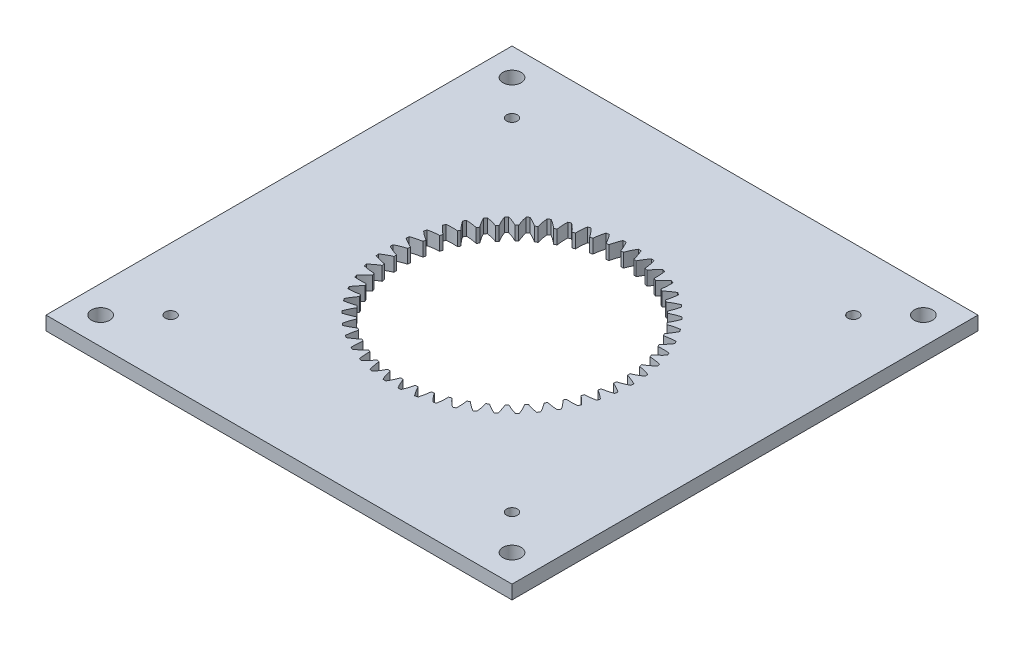
SolidWorks part; units mm, degrees
material "Acrylic (Medium-high impact)"
ref_plane "Front Plane" through (0, 0, 0) normal (0, 0, 1) x (1, 0, 0)
ref_plane "Top Plane" through (0, 0, 0) normal (0, 1, 0) x (1, 0, 0)
ref_plane "Right Plane" through (0, 0, 0) normal (1, 0, 0) x (0, 0, -1)
sketch "Sketch1" plane through (0, 0, 0) normal (0, 1, 0) x (1, 0, 0)
  line L1 (-50.8, 50.8) -> (50.8, 50.8)
  line L2 (-50.8, 50.8) -> (-50.8, -50.8)
  line L3 (-50.8, -50.8) -> (50.8, -50.8)
  line L4 (50.8, 50.8) -> (50.8, -50.8)
  line L5 (-50.8, 50.8) -> (50.8, -50.8) construction
  line L6 (-50.8, -50.8) -> (50.8, 50.8) construction
  point P0 (0, 0)
  dimension "D1" = 101.6
  dimension "D2" = 101.6
extrude "Boss-Extrude1" add sketch "Sketch1" along normal blind 3
extrude "Cut-Extrude2" cut sketch "Sketch3" against normal through all
sketch "Sketch3" plane through (-45.1098, 10, -77.0657) normal (0, 1, 0) x (1, 0, 0)
  arc A17 (36.701, -52.1979) -> (36.5419, -54.6472) centre (49.0349, -54.2291) ccw
  arc A18 (36.009, -54.8582) -> (34.2163, -53.1817) centre (26.6157, -63.1054) ccw
  arc A19 (36.5419, -54.6472) -> (36.009, -54.8582) centre (45.1098, -77.0657) ccw
  arc A20 (34.2163, -53.1817) -> (33.6506, -53.4479) centre (45.1098, -77.0657) ccw
  arc A25 (31.3088, -54.7353) -> (30.7808, -55.0704) centre (45.1098, -77.0657) ccw
  arc A26 (33.6506, -53.4479) -> (33.7997, -55.8978) centre (46.1418, -53.9172) ccw
  arc A27 (33.7997, -55.8978) -> (33.2974, -56.1739) centre (45.1098, -77.0657) ccw
  arc A28 (33.2974, -56.1739) -> (31.3088, -54.7353) centre (25.0119, -65.5334) ccw
  arc A29 (39.8841, -51.3401) -> (39.4193, -53.7501) centre (51.8662, -54.9011) ccw
  arc A30 (38.8641, -53.8927) -> (37.2957, -52.0047) centre (28.5113, -60.8976) ccw
  arc A31 (39.4193, -53.7501) -> (38.8641, -53.8927) centre (45.1098, -77.0657) ccw
  arc A32 (37.2957, -52.0047) -> (36.701, -52.1979) centre (45.1098, -77.0657) ccw
  arc A33 (43.1496, -50.888) -> (42.3864, -53.2208) centre (54.5909, -55.9227) ccw
  arc A34 (41.8177, -53.2926) -> (40.4983, -51.223) centre (30.6685, -58.9447) ccw
  arc A35 (42.3864, -53.2208) -> (41.8177, -53.2926) centre (45.1098, -77.0657) ccw
  arc A36 (40.4983, -51.223) -> (39.8841, -51.3401) centre (45.1098, -77.0657) ccw
  arc A37 (46.446, -50.8488) -> (45.3964, -53.0675) centre (57.166, -57.2777) ccw
  arc A38 (44.8232, -53.0675) -> (43.7736, -50.8488) centre (33.0536, -57.2777) ccw
  arc A39 (45.3964, -53.0675) -> (44.8232, -53.0675) centre (45.1098, -77.0657) ccw
  arc A40 (43.7736, -50.8488) -> (43.1496, -50.888) centre (45.1098, -77.0657) ccw
  arc A41 (49.7213, -51.223) -> (48.4019, -53.2926) centre (59.5511, -58.9447) ccw
  arc A42 (47.8333, -53.2208) -> (47.07, -50.888) centre (35.6288, -55.9227) ccw
  arc A43 (48.4019, -53.2926) -> (47.8333, -53.2208) centre (45.1098, -77.0657) ccw
  arc A44 (47.07, -50.888) -> (46.446, -50.8488) centre (45.1098, -77.0657) ccw
  arc A45 (52.9239, -52.0047) -> (51.3555, -53.8927) centre (61.7083, -60.8976) ccw
  arc A46 (50.8003, -53.7501) -> (50.3355, -51.3401) centre (38.3534, -54.9011) ccw
  arc A47 (51.3555, -53.8927) -> (50.8003, -53.7501) centre (45.1098, -77.0657) ccw
  arc A48 (50.3355, -51.3401) -> (49.7213, -51.223) centre (45.1098, -77.0657) ccw
  arc A49 (56.0033, -53.1817) -> (54.2106, -54.8582) centre (63.6039, -63.1054) ccw
  arc A50 (53.6777, -54.6472) -> (53.5186, -52.1979) centre (41.1847, -54.2291) ccw
  arc A51 (54.2106, -54.8582) -> (53.6777, -54.6472) centre (45.1098, -77.0657) ccw
  arc A52 (53.5186, -52.1979) -> (52.9239, -52.0047) centre (45.1098, -77.0657) ccw
  arc A53 (58.9108, -54.7353) -> (56.9222, -56.1739) centre (65.2077, -65.5334) ccw
  arc A54 (56.4199, -55.8978) -> (56.569, -53.4479) centre (44.0778, -53.9172) ccw
  arc A55 (56.9222, -56.1739) -> (56.4199, -55.8978) centre (45.1098, -77.0657) ccw
  arc A56 (56.569, -53.4479) -> (56.0033, -53.1817) centre (45.1098, -77.0657) ccw
  arc A57 (61.6007, -56.6411) -> (59.4475, -57.8192) centre (66.4946, -68.1433) ccw
  arc A58 (58.9838, -57.4823) -> (59.4388, -55.0704) centre (46.9873, -53.9704) ccw
  arc A59 (59.4475, -57.8192) -> (58.9838, -57.4823) centre (45.1098, -77.0657) ccw
  arc A60 (59.4388, -55.0704) -> (58.9108, -54.7353) centre (45.1098, -77.0657) ccw
  arc A61 (64.0306, -58.8691) -> (61.7467, -59.7679) centre (67.4443, -70.8939) ccw
  arc A62 (61.3288, -59.3756) -> (62.0825, -57.0397) centre (49.8671, -54.3878) ccw
  arc A63 (61.7467, -59.7679) -> (61.3288, -59.3756) centre (45.1098, -77.0657) ccw
  arc A64 (62.0825, -57.0397) -> (61.6007, -56.6411) centre (45.1098, -77.0657) ccw
  arc A65 (66.162, -61.384) -> (63.7835, -61.9895) centre (68.0417, -73.7418) ccw
  arc A66 (63.4181, -61.5478) -> (64.4586, -59.3249) centre (52.6719, -55.1629) ccw
  arc A67 (63.7835, -61.9895) -> (63.4181, -61.5478) centre (45.1098, -77.0657) ccw
  arc A68 (64.4586, -59.3249) -> (64.0306, -58.8691) centre (45.1098, -77.0657) ccw
  arc A69 (67.9615, -64.1462) -> (65.5258, -64.4488) centre (68.2775, -76.6422) ccw
  arc A70 (65.2187, -63.9648) -> (66.5296, -61.8898) centre (55.3574, -56.2834) ccw
  arc A71 (65.5258, -64.4488) -> (65.2187, -63.9648) centre (45.1098, -77.0657) ccw
  arc A72 (66.5296, -61.8898) -> (66.162, -61.384) centre (45.1098, -77.0657) ccw
  arc A73 (69.4005, -67.1121) -> (66.9461, -67.1071) centre (68.1479, -79.5492) ccw
  arc A74 (66.7021, -66.5884) -> (68.2627, -64.6941) centre (57.8813, -57.7316) ccw
  arc A75 (66.9461, -67.1071) -> (66.7021, -66.5884) centre (45.1098, -77.0657) ccw
  arc A76 (68.2627, -64.6941) -> (67.9615, -64.1462) centre (45.1098, -77.0657) ccw
  arc A77 (70.4565, -70.235) -> (68.0221, -69.9224) centre (67.655, -82.417) ccw
  arc A78 (67.845, -69.3773) -> (69.6307, -67.6935) centre (60.2038, -59.4847) ccw
  arc A79 (68.0221, -69.9224) -> (67.845, -69.3773) centre (45.1098, -77.0657) ccw
  arc A80 (69.6307, -67.6935) -> (69.4005, -67.1121) centre (45.1098, -77.0657) ccw
  arc A81 (71.1128, -73.4657) -> (68.7367, -72.8504) centre (66.8065, -85.2005) ccw
  arc A82 (68.6293, -72.2874) -> (70.612, -70.8407) centre (62.2883, -61.5152) ccw
  arc A83 (68.7367, -72.8504) -> (68.6293, -72.2874) centre (45.1098, -77.0657) ccw
  arc A84 (70.612, -70.8407) -> (70.4565, -70.235) centre (45.1098, -77.0657) ccw
  arc A85 (71.3589, -76.7531) -> (69.0787, -75.8449) centre (65.6158, -87.8557) ccw
  arc A86 (69.0427, -75.2728) -> (71.1911, -74.086) centre (64.1018, -63.7908) ccw
  arc A87 (69.0787, -75.8449) -> (69.0427, -75.2728) centre (45.1098, -77.0657) ccw
  arc A88 (71.1911, -74.086) -> (71.1128, -73.4657) centre (45.1098, -77.0657) ccw
  arc A89 (71.1911, -80.0455) -> (69.0427, -78.8586) centre (64.1018, -90.3407) ccw
  arc A90 (69.0787, -78.2866) -> (71.3589, -77.3784) centre (65.6158, -66.2758) ccw
  arc A91 (69.0427, -78.8586) -> (69.0787, -78.2866) centre (45.1098, -77.0657) ccw
  arc A92 (71.3589, -77.3784) -> (71.3589, -76.7531) centre (45.1098, -77.0657) ccw
  arc A93 (70.612, -83.2908) -> (68.6293, -81.8441) centre (62.2883, -92.6163) ccw
  arc A94 (68.7367, -81.2811) -> (71.1128, -80.6658) centre (66.8065, -68.931) ccw
  arc A95 (68.6293, -81.8441) -> (68.7367, -81.2811) centre (45.1098, -77.0657) ccw
  arc A96 (71.1128, -80.6658) -> (71.1911, -80.0455) centre (45.1098, -77.0657) ccw
  arc A97 (69.6307, -86.438) -> (67.845, -84.7542) centre (60.2038, -94.6467) ccw
  arc A98 (68.0221, -84.2091) -> (70.4565, -83.8964) centre (67.655, -71.7144) ccw
  arc A99 (67.845, -84.7542) -> (68.0221, -84.2091) centre (45.1098, -77.0657) ccw
  arc A100 (70.4565, -83.8964) -> (70.612, -83.2908) centre (45.1098, -77.0657) ccw
  arc A101 (68.2627, -89.4374) -> (66.7021, -87.543) centre (57.8813, -96.3999) ccw
  arc A102 (66.9461, -87.0244) -> (69.4005, -87.0194) centre (68.1479, -74.5823) ccw
  arc A103 (66.7021, -87.543) -> (66.9461, -87.0244) centre (45.1098, -77.0657) ccw
  arc A104 (69.4005, -87.0194) -> (69.6307, -86.438) centre (45.1098, -77.0657) ccw
  arc A105 (66.5296, -92.2417) -> (65.2187, -90.1666) centre (55.3574, -97.8481) ccw
  arc A106 (65.5258, -89.6827) -> (67.9615, -89.9853) centre (68.2775, -77.4893) ccw
  arc A107 (65.2187, -90.1666) -> (65.5258, -89.6827) centre (45.1098, -77.0657) ccw
  arc A108 (67.9615, -89.9853) -> (68.2627, -89.4374) centre (45.1098, -77.0657) ccw
  arc A109 (64.4586, -94.8066) -> (63.4181, -92.5836) centre (52.6719, -98.9686) ccw
  arc A110 (63.7835, -92.142) -> (66.162, -92.7475) centre (68.0417, -80.3897) ccw
  arc A111 (63.4181, -92.5836) -> (63.7835, -92.142) centre (45.1098, -77.0657) ccw
  arc A112 (66.162, -92.7475) -> (66.5296, -92.2417) centre (45.1098, -77.0657) ccw
  arc A113 (62.0825, -97.0918) -> (61.3288, -94.7559) centre (49.8671, -99.7437) ccw
  arc A114 (61.7467, -94.3636) -> (64.0306, -95.2624) centre (67.4443, -83.2376) ccw
  arc A115 (61.3288, -94.7559) -> (61.7467, -94.3636) centre (45.1098, -77.0657) ccw
  arc A116 (64.0306, -95.2624) -> (64.4586, -94.8066) centre (45.1098, -77.0657) ccw
  arc A117 (59.4388, -99.0611) -> (58.9838, -96.6492) centre (46.9873, -100.1611) ccw
  arc A118 (59.4475, -96.3123) -> (61.6007, -97.4903) centre (66.4946, -85.9882) ccw
  arc A119 (58.9838, -96.6492) -> (59.4475, -96.3123) centre (45.1098, -77.0657) ccw
  arc A120 (61.6007, -97.4903) -> (62.0825, -97.0918) centre (45.1098, -77.0657) ccw
  arc A121 (56.569, -100.6836) -> (56.4199, -98.2337) centre (44.0778, -100.2143) ccw
  arc A122 (56.9222, -97.9575) -> (58.9108, -99.3961) centre (65.2077, -88.598) ccw
  arc A123 (56.4199, -98.2337) -> (56.9222, -97.9575) centre (45.1098, -77.0657) ccw
  arc A124 (58.9108, -99.3961) -> (59.4388, -99.0611) centre (45.1098, -77.0657) ccw
  arc A125 (53.5186, -101.9335) -> (53.6777, -99.4843) centre (41.1847, -99.9024) ccw
  arc A126 (54.2106, -99.2733) -> (56.0033, -100.9498) centre (63.6039, -91.026) ccw
  arc A127 (53.6777, -99.4843) -> (54.2106, -99.2733) centre (45.1098, -77.0657) ccw
  arc A128 (56.0033, -100.9498) -> (56.569, -100.6836) centre (45.1098, -77.0657) ccw
  arc A129 (50.3355, -102.7914) -> (50.8003, -100.3814) centre (38.3534, -99.2304) ccw
  arc A130 (51.3555, -100.2388) -> (52.9239, -102.1268) centre (61.7083, -93.2339) ccw
  arc A131 (50.8003, -100.3814) -> (51.3555, -100.2388) centre (45.1098, -77.0657) ccw
  arc A132 (52.9239, -102.1268) -> (53.5186, -101.9335) centre (45.1098, -77.0657) ccw
  arc A133 (47.07, -103.2434) -> (47.8333, -100.9107) centre (35.6288, -98.2088) ccw
  arc A134 (48.4019, -100.8389) -> (49.7213, -102.9085) centre (59.5511, -95.1867) ccw
  arc A135 (47.8333, -100.9107) -> (48.4019, -100.8389) centre (45.1098, -77.0657) ccw
  arc A136 (49.7213, -102.9085) -> (50.3355, -102.7914) centre (45.1098, -77.0657) ccw
  arc A137 (43.7736, -103.2827) -> (44.8232, -101.064) centre (33.0536, -96.8538) ccw
  arc A138 (45.3964, -101.064) -> (46.446, -103.2827) centre (57.166, -96.8538) ccw
  arc A139 (44.8232, -101.064) -> (45.3964, -101.064) centre (45.1098, -77.0657) ccw
  arc A140 (46.446, -103.2827) -> (47.07, -103.2434) centre (45.1098, -77.0657) ccw
  arc A141 (40.4983, -102.9085) -> (41.8177, -100.8389) centre (30.6685, -95.1867) ccw
  arc A142 (42.3864, -100.9107) -> (43.1496, -103.2434) centre (54.5909, -98.2088) ccw
  arc A143 (41.8177, -100.8389) -> (42.3864, -100.9107) centre (45.1098, -77.0657) ccw
  arc A144 (43.1496, -103.2434) -> (43.7736, -103.2827) centre (45.1098, -77.0657) ccw
  arc A145 (37.2957, -102.1268) -> (38.8641, -100.2388) centre (28.5113, -93.2339) ccw
  arc A146 (39.4193, -100.3814) -> (39.8841, -102.7914) centre (51.8662, -99.2304) ccw
  arc A147 (38.8641, -100.2388) -> (39.4193, -100.3814) centre (45.1098, -77.0657) ccw
  arc A148 (39.8841, -102.7914) -> (40.4983, -102.9085) centre (45.1098, -77.0657) ccw
  arc A149 (34.2163, -100.9498) -> (36.009, -99.2733) centre (26.6157, -91.026) ccw
  arc A150 (36.5419, -99.4843) -> (36.701, -101.9335) centre (49.0349, -99.9024) ccw
  arc A151 (36.009, -99.2733) -> (36.5419, -99.4843) centre (45.1098, -77.0657) ccw
  arc A152 (36.701, -101.9335) -> (37.2957, -102.1268) centre (45.1098, -77.0657) ccw
  arc A153 (31.3088, -99.3961) -> (33.2974, -97.9575) centre (25.0119, -88.598) ccw
  arc A154 (33.7997, -98.2337) -> (33.6506, -100.6836) centre (46.1418, -100.2143) ccw
  arc A155 (33.2974, -97.9575) -> (33.7997, -98.2337) centre (45.1098, -77.0657) ccw
  arc A156 (33.6506, -100.6836) -> (34.2163, -100.9498) centre (45.1098, -77.0657) ccw
  arc A157 (28.6189, -97.4903) -> (30.7721, -96.3123) centre (23.725, -85.9882) ccw
  arc A158 (31.2358, -96.6492) -> (30.7808, -99.0611) centre (43.2324, -100.1611) ccw
  arc A159 (30.7721, -96.3123) -> (31.2358, -96.6492) centre (45.1098, -77.0657) ccw
  arc A160 (30.7808, -99.0611) -> (31.3088, -99.3961) centre (45.1098, -77.0657) ccw
  arc A161 (26.189, -95.2624) -> (28.4729, -94.3636) centre (22.7753, -83.2376) ccw
  arc A162 (28.8908, -94.7559) -> (28.1371, -97.0918) centre (40.3525, -99.7437) ccw
  arc A163 (28.4729, -94.3636) -> (28.8908, -94.7559) centre (45.1098, -77.0657) ccw
  arc A164 (28.1371, -97.0918) -> (28.6189, -97.4903) centre (45.1098, -77.0657) ccw
  arc A165 (24.0576, -92.7475) -> (26.4361, -92.142) centre (22.1779, -80.3897) ccw
  arc A166 (26.8015, -92.5836) -> (25.761, -94.8066) centre (37.5478, -98.9686) ccw
  arc A167 (26.4361, -92.142) -> (26.8015, -92.5836) centre (45.1098, -77.0657) ccw
  arc A168 (25.761, -94.8066) -> (26.189, -95.2624) centre (45.1098, -77.0657) ccw
  arc A169 (22.2581, -89.9853) -> (24.6938, -89.6827) centre (21.9421, -77.4893) ccw
  arc A170 (25.0009, -90.1666) -> (23.69, -92.2417) centre (34.8622, -97.8481) ccw
  arc A171 (24.6938, -89.6827) -> (25.0009, -90.1666) centre (45.1098, -77.0657) ccw
  arc A172 (23.69, -92.2417) -> (24.0576, -92.7475) centre (45.1098, -77.0657) ccw
  arc A173 (20.8191, -87.0194) -> (23.2735, -87.0244) centre (22.0717, -74.5823) ccw
  arc A174 (23.5175, -87.543) -> (21.9569, -89.4374) centre (32.3383, -96.3999) ccw
  arc A175 (23.2735, -87.0244) -> (23.5175, -87.543) centre (45.1098, -77.0657) ccw
  arc A176 (21.9569, -89.4374) -> (22.2581, -89.9853) centre (45.1098, -77.0657) ccw
  arc A177 (19.7631, -83.8964) -> (22.1975, -84.2091) centre (22.5647, -71.7144) ccw
  arc A178 (22.3746, -84.7542) -> (20.5889, -86.438) centre (30.0158, -94.6467) ccw
  arc A179 (22.1975, -84.2091) -> (22.3746, -84.7542) centre (45.1098, -77.0657) ccw
  arc A180 (20.5889, -86.438) -> (20.8191, -87.0194) centre (45.1098, -77.0657) ccw
  arc A181 (19.1068, -80.6658) -> (21.4829, -81.2811) centre (23.4131, -68.931) ccw
  arc A182 (21.5903, -81.8441) -> (19.6076, -83.2908) centre (27.9313, -92.6163) ccw
  arc A183 (21.4829, -81.2811) -> (21.5903, -81.8441) centre (45.1098, -77.0657) ccw
  arc A184 (19.6076, -83.2908) -> (19.7631, -83.8964) centre (45.1098, -77.0657) ccw
  arc A185 (18.8607, -77.3784) -> (21.1409, -78.2866) centre (24.6038, -66.2758) ccw
  arc A186 (21.1769, -78.8586) -> (19.0285, -80.0455) centre (26.1178, -90.3407) ccw
  arc A187 (21.1409, -78.2866) -> (21.1769, -78.8586) centre (45.1098, -77.0657) ccw
  arc A188 (19.0285, -80.0455) -> (19.1068, -80.6658) centre (45.1098, -77.0657) ccw
  arc A189 (19.0285, -74.086) -> (21.1769, -75.2728) centre (26.1178, -63.7908) ccw
  arc A190 (21.1409, -75.8449) -> (18.8607, -76.7531) centre (24.6038, -87.8557) ccw
  arc A191 (21.1769, -75.2728) -> (21.1409, -75.8449) centre (45.1098, -77.0657) ccw
  arc A192 (18.8607, -76.7531) -> (18.8607, -77.3784) centre (45.1098, -77.0657) ccw
  arc A193 (19.6076, -70.8407) -> (21.5903, -72.2874) centre (27.9313, -61.5152) ccw
  arc A194 (21.4829, -72.8504) -> (19.1068, -73.4657) centre (23.4131, -85.2005) ccw
  arc A195 (21.5903, -72.2874) -> (21.4829, -72.8504) centre (45.1098, -77.0657) ccw
  arc A196 (19.1068, -73.4657) -> (19.0285, -74.086) centre (45.1098, -77.0657) ccw
  arc A197 (20.5889, -67.6935) -> (22.3746, -69.3773) centre (30.0158, -59.4847) ccw
  arc A198 (22.1975, -69.9224) -> (19.7631, -70.235) centre (22.5647, -82.417) ccw
  arc A199 (22.3746, -69.3773) -> (22.1975, -69.9224) centre (45.1098, -77.0657) ccw
  arc A200 (19.7631, -70.235) -> (19.6076, -70.8407) centre (45.1098, -77.0657) ccw
  arc A201 (21.9569, -64.6941) -> (23.5175, -66.5884) centre (32.3383, -57.7316) ccw
  arc A202 (23.2735, -67.1071) -> (20.8191, -67.1121) centre (22.0717, -79.5492) ccw
  arc A203 (23.5175, -66.5884) -> (23.2735, -67.1071) centre (45.1098, -77.0657) ccw
  arc A204 (20.8191, -67.1121) -> (20.5889, -67.6935) centre (45.1098, -77.0657) ccw
  arc A205 (23.69, -61.8898) -> (25.0009, -63.9648) centre (34.8622, -56.2834) ccw
  arc A206 (24.6938, -64.4488) -> (22.2581, -64.1462) centre (21.9421, -76.6422) ccw
  arc A207 (25.0009, -63.9648) -> (24.6938, -64.4488) centre (45.1098, -77.0657) ccw
  arc A208 (22.2581, -64.1462) -> (21.9569, -64.6941) centre (45.1098, -77.0657) ccw
  arc A209 (25.761, -59.3249) -> (26.8015, -61.5478) centre (37.5478, -55.1629) ccw
  arc A210 (26.4361, -61.9895) -> (24.0576, -61.384) centre (22.1779, -73.7418) ccw
  arc A211 (26.8015, -61.5478) -> (26.4361, -61.9895) centre (45.1098, -77.0657) ccw
  arc A212 (24.0576, -61.384) -> (23.69, -61.8898) centre (45.1098, -77.0657) ccw
  arc A213 (28.1371, -57.0397) -> (28.8908, -59.3756) centre (40.3525, -54.3878) ccw
  arc A214 (28.4729, -59.7679) -> (26.189, -58.8691) centre (22.7753, -70.8939) ccw
  arc A215 (28.8908, -59.3756) -> (28.4729, -59.7679) centre (45.1098, -77.0657) ccw
  arc A216 (26.189, -58.8691) -> (25.761, -59.3249) centre (45.1098, -77.0657) ccw
  arc A217 (30.7808, -55.0704) -> (31.2358, -57.4823) centre (43.2324, -53.9704) ccw
  arc A218 (30.7721, -57.8192) -> (28.6189, -56.6411) centre (23.725, -68.1433) ccw
  arc A219 (31.2358, -57.4823) -> (30.7721, -57.8192) centre (45.1098, -77.0657) ccw
  arc A220 (28.6189, -56.6411) -> (28.1371, -57.0397) centre (45.1098, -77.0657) ccw
  point P354 (45.1098, -77.0657)
extrude "Cut-Extrude3" cut sketch "Sketch4" against normal blind 100
sketch "Sketch4" plane through (23.8049, -0.7366, -67.6554) normal (0, -1, 0) x (0.7071, 0, -0.7071)
  circle A8 centre (-64.6722, 94.4256) radius 1.9844
  circle A9 centre (-1.2536, 31.0071) radius 1.9844
  circle A11 centre (-64.6722, 83.6314) radius 1.1906
  circle A12 centre (-12.0479, 31.0071) radius 1.1906
  circle A13 centre (-64.6722, -32.4115) radius 1.9844
  circle A14 centre (-64.6722, -21.6172) radius 1.1906
  circle A15 centre (-128.0908, 31.0071) radius 1.9844
  circle A16 centre (-117.2965, 31.0071) radius 1.1906
  point P21 (-64.6722, 31.0071)
